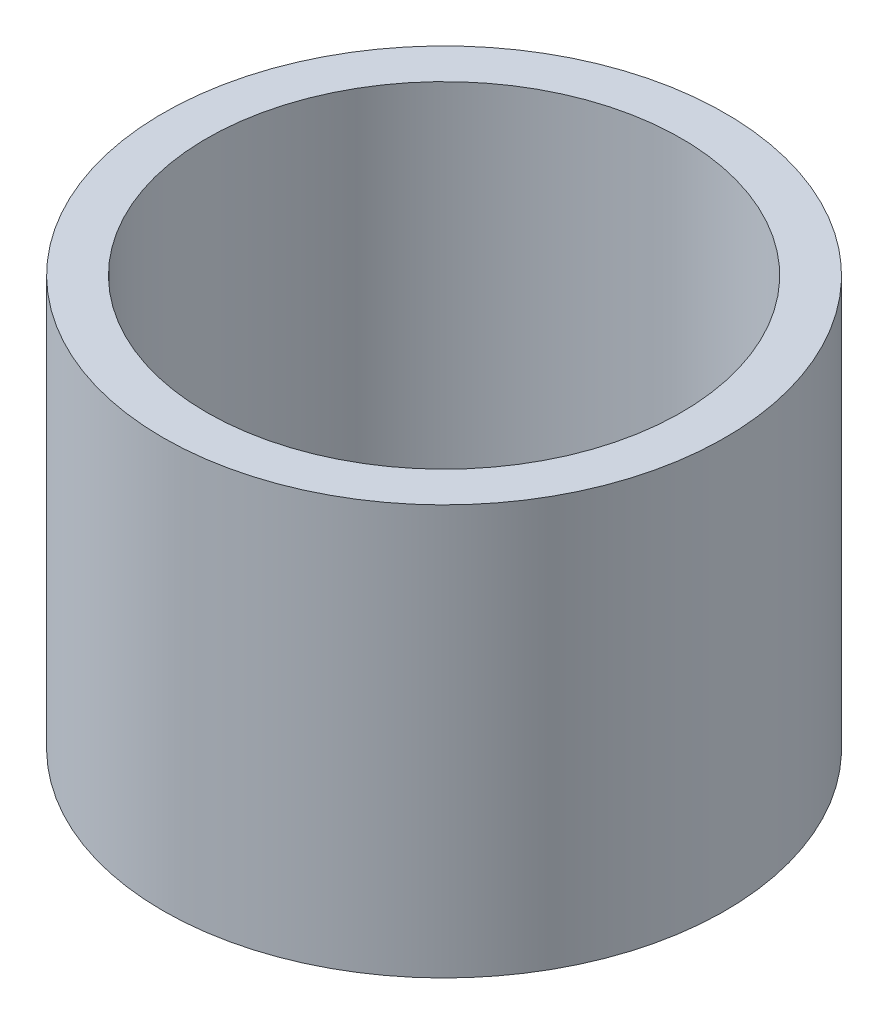
SolidWorks part; units mm, degrees
ref_plane "Front Plane" through (0, 0, 0) normal (0, 0, 1) x (1, 0, 0)
ref_plane "Top Plane" through (0, 0, 0) normal (0, 1, 0) x (1, 0, 0)
ref_plane "Right Plane" through (0, 0, 0) normal (1, 0, 0) x (0, 0, -1)
sketch "Sketch1" plane through (0, 0, 0) normal (0, 1, 0) x (1, 0, 0)
  circle A0 centre (0, 0) radius 28.575
  dimension "D1" = 57.15
extrude "Boss-Extrude1" add sketch "Sketch1" along normal blind 41.656
sketch "Sketch2" plane through (0, 41.656, 0) normal (0, 1, 0) x (1, 0, 0)
  circle A0 centre (0, 0) radius 24.13
  dimension "D1" = 48.26
extrude "Cut-Extrude1" cut sketch "Sketch2" against normal blind 35.2654 contours A0
